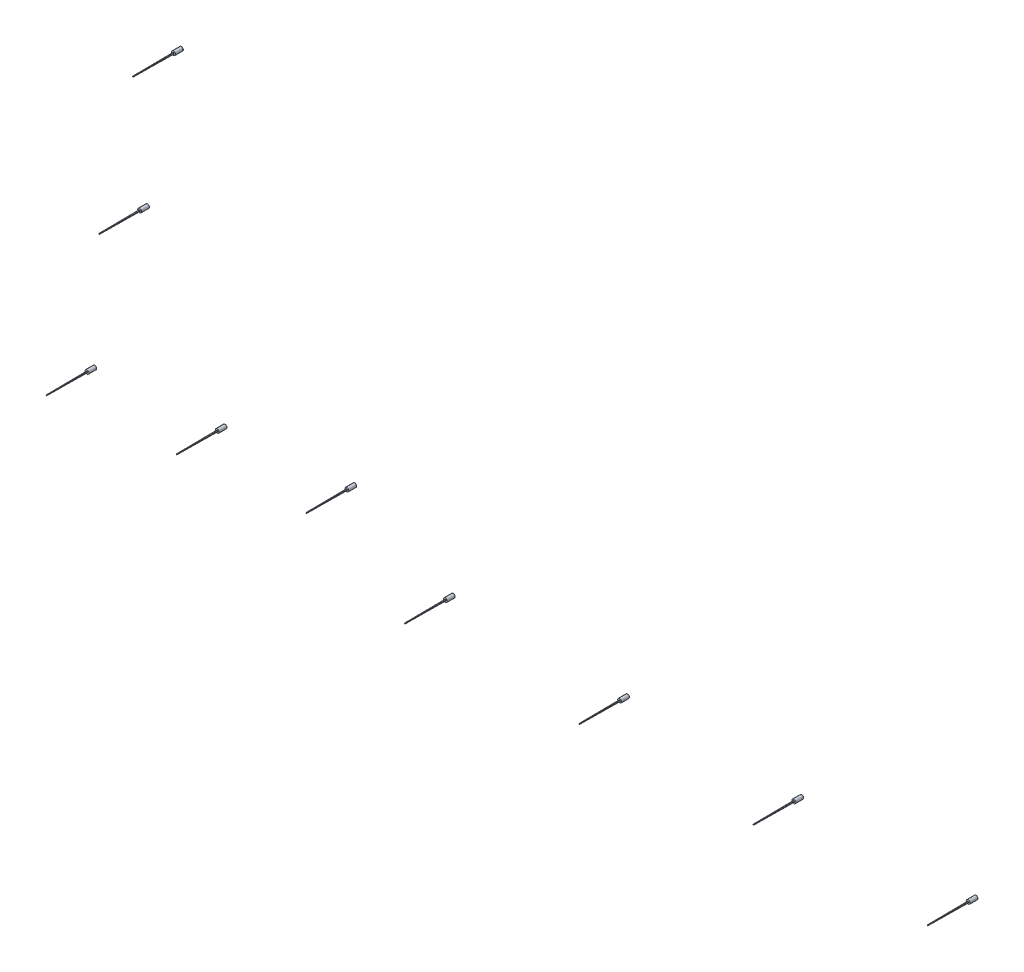
SolidWorks part; units mm, degrees
ref_plane "Alzado" through (0, 0, 0) normal (0, 0, 1) x (1, 0, 0)
ref_plane "Planta" through (0, 0, 0) normal (0, 1, 0) x (1, 0, 0)
ref_plane "Vista lateral" through (0, 0, 0) normal (1, 0, 0) x (0, 0, -1)
sketch "Croquis1" plane through (0, 0, 0) normal (0, 0, 1) x (1, 0, 0)
  line L2 (88.617, 158.8144) -> (-93.2288, 156.1518)
  line L3 (-93.2288, 156.1518) -> (-181.8458, -2.6626)
  line L4 (-181.8458, -2.6626) -> (-88.617, -158.8144)
  line L5 (-88.617, -158.8144) -> (93.2288, -156.1518)
  line L6 (93.2288, -156.1518) -> (181.8458, 2.6626)
  line L7 (181.8458, 2.6626) -> (88.617, 158.8144)
  line L8 (-39933.4232, 169.241) -> (-40113.2786, 142.2777)
  line L9 (-40113.2786, 142.2777) -> (-40179.8554, -26.9633)
  line L10 (-40179.8554, -26.9633) -> (-40066.5768, -169.241)
  line L11 (-40066.5768, -169.241) -> (-39886.7214, -142.2777)
  line L12 (-39886.7214, -142.2777) -> (-39820.1446, 26.9633)
  line L13 (-39820.1446, 26.9633) -> (-39933.4232, 169.241)
  line L14 (-182312.7649, 77664.4905) -> (-182494.5809, 77660.2518)
  line L15 (-79908.3117, 157.0613) -> (-80090.1749, 157.9351)
  line L16 (-80090.1749, 157.9351) -> (-80181.8632, 0.8737)
  line L17 (-80181.8632, 0.8737) -> (-80091.6883, -157.0613)
  line L18 (-80091.6883, -157.0613) -> (-79909.8251, -157.9351)
  line L19 (-79909.8251, -157.9351) -> (-79818.1368, -0.8737)
  line L20 (-79818.1368, -0.8737) -> (-79908.3117, 157.0613)
  line L21 (-182494.5809, 77660.2518) -> (-182581.8179, 77500.6752)
  line L22 (-119896.1728, 149.3148) -> (-120077.3969, 164.5744)
  line L23 (-120077.3969, 164.5744) -> (-120181.224, 15.2595)
  line L24 (-120181.224, 15.2595) -> (-120103.8272, -149.3148)
  line L25 (-120103.8272, -149.3148) -> (-119922.6031, -164.5744)
  line L26 (-119922.6031, -164.5744) -> (-119818.776, -15.2595)
  line L27 (-119818.776, -15.2595) -> (-119896.1728, 149.3148)
  line L28 (-142531.5842, 10809.9202) -> (-142713.3819, 10804.9627)
  line L29 (-142713.3819, 10804.9627) -> (-142799.9875, 10645.0425)
  line L30 (-142799.9875, 10645.0425) -> (-142704.7953, 10490.0798)
  line L31 (-142704.7953, 10490.0798) -> (-142522.9975, 10495.0373)
  line L32 (-142522.9975, 10495.0373) -> (-142436.392, 10654.9575)
  line L35 (-190012.7149, 42422.3709) -> (-190164.7135, 42522.2279)
  line L36 (-182581.8179, 77500.6752) -> (-182487.2391, 77345.3373)
  line L37 (-182487.2391, 77345.3373) -> (-182305.4232, 77349.5761)
  line L38 (-190164.7135, 42522.2279) -> (-190327.1915, 42440.5217)
  line L39 (-182305.4232, 77349.5761) -> (-182218.1861, 77509.1527)
  line L40 (-182218.1861, 77509.1527) -> (-182312.7649, 77664.4905)
  line L43 (-172211.6186, 7341.4683) -> (-172202.0405, 7523.0812)
  line L44 (-172202.0405, 7523.0812) -> (-172354.5329, 7622.1826)
  line L45 (-172354.5329, 7622.1826) -> (-172516.6034, 7539.671)
  line L46 (-172516.6034, 7539.671) -> (-172526.1815, 7358.058)
  line L47 (-172526.1815, 7358.058) -> (-172373.6891, 7258.9567)
  line L48 (-172373.6891, 7258.9567) -> (-172211.6186, 7341.4683)
  line L49 (-202157.3303, 4354.8495) -> (-202336.9184, 4383.54)
  line L50 (-202336.9184, 4383.54) -> (-202451.559, 4242.3574)
  line L51 (-202451.559, 4242.3574) -> (-202386.6116, 4072.4844)
  line L52 (-202386.6116, 4072.4844) -> (-202207.0236, 4043.794)
  line L53 (-202207.0236, 4043.794) -> (-202092.3829, 4184.9765)
  line L54 (-190327.1915, 42440.5217) -> (-190337.6708, 42258.9585)
  line L55 (-190337.6708, 42258.9585) -> (-190185.6722, 42159.1016)
  line L56 (-190185.6722, 42159.1016) -> (-190023.1942, 42240.8078)
  line L57 (-142436.392, 10654.9575) -> (-142531.5842, 10809.9202)
  line L58 (-190023.1942, 42240.8078) -> (-190012.7149, 42422.3709)
  line L68 (-202092.3829, 4184.9765) -> (-202157.3303, 4354.8495)
  circle A0 centre (0, 0) radius 157.5 construction
  circle A1 centre (-40000, 0) radius 157.5 construction
  circle A2 centre (-80000, 0) radius 157.5 construction
  circle A3 centre (-120000, 0) radius 157.5 construction
  arc A4 (-182400.002, 77347.4139) -> (-182534.5285, 77423.0062) centre (-182400.002, 77504.9139) ccw construction
  circle A5 centre (-172364.111, 7440.5696) radius 157.5 construction
  circle A6 centre (-202271.971, 4213.667) radius 157.5 construction
  circle A7 centre (-190175.1928, 42340.6647) radius 157.5 construction
  circle A9 centre (-142618.1897, 10650) radius 157.5 construction
  dimension "D1" = 40000
  dimension "D2" = 315
  dimension "D3" = 315
  dimension "D4" = 40000
  dimension "D5" = 315
  dimension "D6" = 40000
  dimension "D7" = 315
  dimension "D9" = 315
  dimension "D10" = 315
  dimension "D11" = 60000
  dimension "D12" = 315
  dimension "D13" = 40000
  dimension "D14" = 315
  dimension "D15" = 315
extrude "Saliente-Extruir1" add sketch "Croquis1" along normal blind 11000 draft 0.39
sketch "Croquis9" plane through (0, 0, 0) normal (0, 0, -1) x (-1, 0, 0)
  circle A0 centre (0, 0) radius 450
  circle A1 centre (40000, 0) radius 450
  circle A2 centre (80000, 0) radius 450
  circle A3 centre (120000, 0) radius 450
  circle A4 centre (142622.483, 10652.3251) radius 450
  circle A5 centre (172364.111, 7440.5696) radius 450
  circle A6 centre (202271.971, 4213.667) radius 450
  circle A7 centre (190175.1928, 42340.6647) radius 450
  circle A8 centre (185900.002, 77404.9139) radius 450
  dimension "D1" = 900
  dimension "D2" = 900
  dimension "D3" = 900
  dimension "D4" = 900
  dimension "D5" = 900
  dimension "D6" = 900
  dimension "D7" = 900
  dimension "D8" = 900
  dimension "D9" = 900
extrude "Saliente-Extruir8" add sketch "Croquis9" against normal blind 1700
sketch "Croquis10" plane through (0, 0, 0) normal (0, 0, -1) x (-1, 0, 0)
  circle A0 centre (0, 0) radius 455
  circle A1 centre (40000, 0) radius 455
  circle A2 centre (80000, 0) radius 455
  circle A3 centre (120000, 0) radius 455
  circle A4 centre (142622.483, 10652.3251) radius 455
  circle A5 centre (172364.111, 7440.5696) radius 455
  circle A6 centre (202271.971, 4213.667) radius 455
  circle A7 centre (190175.1928, 42340.6647) radius 455
  circle A8 centre (185900.002, 77404.9139) radius 455
  dimension "D1" = 910
  dimension "D2" = 910
  dimension "D3" = 910
  dimension "D4" = 910
  dimension "D5" = 910
  dimension "D6" = 910
  dimension "D7" = 910
  dimension "D8" = 910
  dimension "D9" = 910
extrude "Saliente-Extruir9" add sketch "Croquis10" along normal blind 100
sketch "Croquis11" plane through (0, 0, 1700) normal (0, 0, 1) x (1, 0, 0)
  circle A0 centre (-185902.9635, 77444.1353) radius 574.0124
extrude "Cortar-Extruir1" cut sketch "Croquis11" against normal blind 3000
sketch "Croquis12" plane through (0, 0, 0) normal (0, 0, -1) x (-1, 0, 0)
  circle A0 centre (182403.6729, 77506.9207) radius 450
  dimension "D1" = 900
extrude "Saliente-Extruir10" add sketch "Croquis12" against normal blind 1700
sketch "Croquis13" plane through (0, 0, 0) normal (0, 0, -1) x (-1, 0, 0)
  circle A0 centre (182403.6729, 77506.9207) radius 455
  dimension "D1" = 910
extrude "Saliente-Extruir11" add sketch "Croquis13" along normal blind 100
